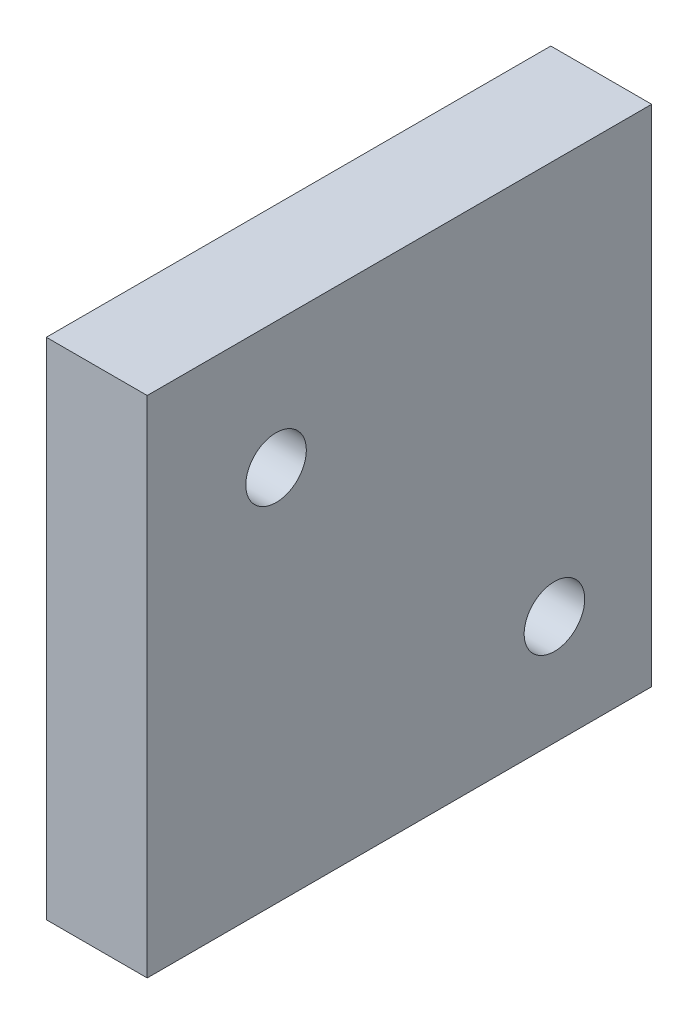
SolidWorks part; units mm, degrees
ref_plane "Front Plane" through (0, 0, 0) normal (1, 0, 0) x (0, 1, 0)
ref_plane "Top Plane" through (0, 0, 0) normal (0, 0, 1) x (0, 1, 0)
ref_plane "Right Plane" through (0, 0, 0) normal (0, 1, 0) x (-1, 0, 0)
sketch "Sketch1" plane through (0, 0, 0) normal (1, 0, 0) x (0, 1, 0)
  line L1 (-85.8822, 54.7445) -> (14.1178, 54.7445)
  line L2 (-85.8822, 54.7445) -> (-85.8822, -45.2555)
  line L3 (-85.8822, -45.2555) -> (14.1178, -45.2555)
  line L4 (14.1178, 54.7445) -> (14.1178, -45.2555)
  dimension "D1" = 100
  dimension "D2" = 100
extrude "Boss-Extrude1" add sketch "Sketch1" along normal blind 20
hole_wizard "Ø12.0 (12) Diameter Hole1" positions "Sketch2" profile "Sketch3" hole size "Ø12.0" standard "ISO" end condition through all
sketch "Sketch2" plane through (20, 0, 0) normal (1, 0, 0) x (0, 1, 0)
  point P0 (-11.0343, 29.2005)
  point P2 (-64.179, -25.9822)
sketch "Sketch3" plane through (20, -11.0343, 29.2005) normal (0, 1, 0) x (0, 0, -1)
  line L0 (0, 0) -> (0, 20)
  line L1 (0, 20) -> (6, 20)
  line L2 (6, 20) -> (6, 0)
  line L5 (6, 0) -> (0, 0)
  line L11 (0, -6.35) -> (0, 107.95) construction
  dimension "Thru Hole Dia." = 12
  dimension "Thru Hole Depth" = 20
